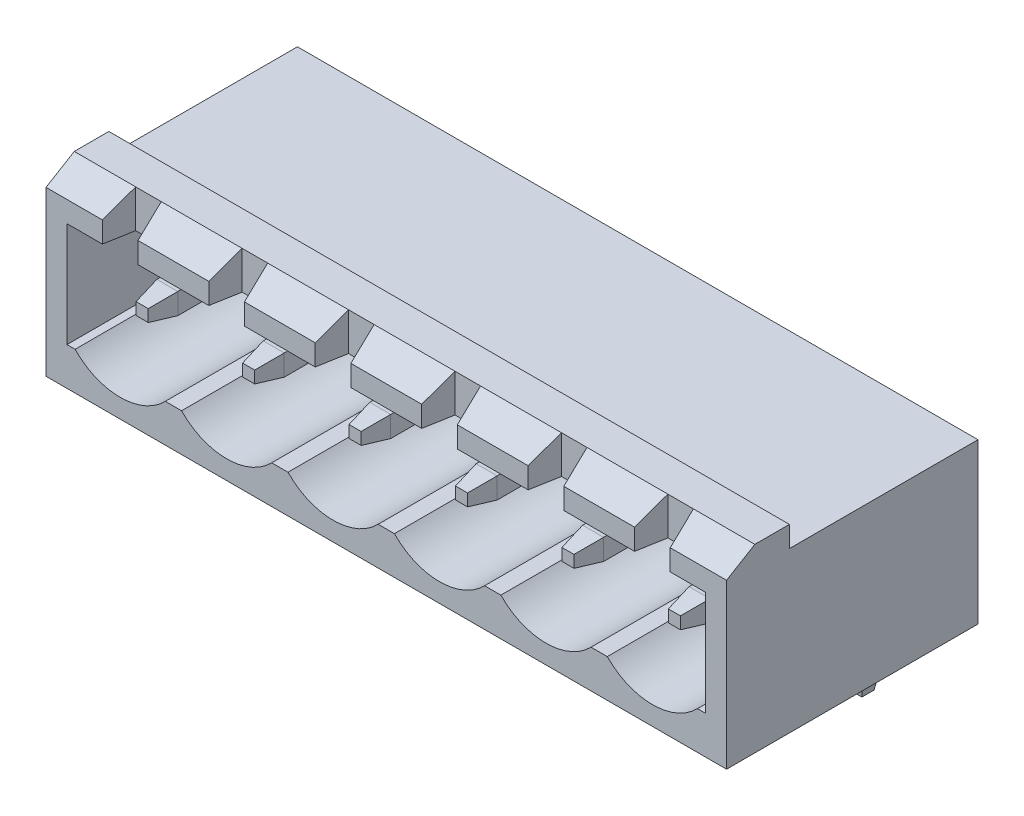
SolidWorks part; units mm, degrees
ref_plane "Front Plane" through (0, 0, 0) normal (0, 0, 1) x (1, 0, 0)
ref_plane "Top Plane" through (0, 0, 0) normal (0, 1, 0) x (1, 0, 0)
ref_plane "Right Plane" through (0, 0, 0) normal (1, 0, 0) x (0, 0, -1)
sketch "Sketch1" plane through (0, 0, 0) normal (0, 0, 1) x (1, 0, 0)
  line L1 (16.24, -3.81) -> (-16.24, -3.81)
  line L2 (16.24, -3.81) -> (16.24, 3.81)
  line L3 (16.24, 3.81) -> (-16.24, 3.81)
  line L4 (-16.24, -3.81) -> (-16.24, 3.81)
  line L5 (16.24, -3.81) -> (-16.24, 3.81) construction
  line L6 (16.24, 3.81) -> (-16.24, -3.81) construction
  point P0 (0, 0)
  dimension "D1" = 7.62
  dimension "D2" = 32.48
extrude "Boss-Extrude1" add sketch "Sketch1" along normal mid plane 12
sketch "Sketch7" plane through (16.24, 0, 0) normal (1, 0, 0) x (0, 0, -1)
  line L0 (-6, 3.81) -> (-6, 4)
  line L1 (-3, 4.81) -> (-6, 4.81) construction
  line L2 (-3, 4.81) -> (-3, 3.81) construction
  line L3 (-3, 3.81) -> (-6, 3.81) construction
  line L4 (-6, 4.81) -> (-6, 3.81) construction
  line L5 (-3, 4.81) -> (-6, 3.81) construction
  line L6 (-3, 3.81) -> (-6, 4.81) construction
  line L7 (-6, 4) -> (-4.65, 4.81)
  line L8 (-4.65, 4.81) -> (-3, 4.81)
  line L9 (-3, 4.81) -> (-3, 3.81)
  line L10 (-3, 3.81) -> (-6, 3.81)
  point P0 (-4.5, 4.31)
  point P6 (0, 0)
  dimension "D1" = 1
  dimension "D2" = 3
  dimension "D3" = 1.65
  dimension "D4" = 0.81
extrude "Boss-Extrude6" add sketch "Sketch7" against normal up to surface (32.48 mm away) up to face at (-16.24, 0, 0)
sketch "Sketch2" plane through (0, 0, 6) normal (0, 0, 1) x (1, 0, 0)
  line L0 (16.24, -3.81) -> (16.24, 4) construction
  line L1 (15.24, -2) -> (10.16, -2) construction
  line L2 (15.24, -2) -> (15.24, 3) construction
  line L3 (15.24, 3) -> (10.16, 3) construction
  line L4 (10.16, -2) -> (10.16, 3) construction
  line L5 (15.24, -2) -> (10.16, 3) construction
  line L6 (15.24, 3) -> (10.16, -2) construction
  line L7 (16.24, 3.81) -> (-16.24, 3.81) construction
  line L8 (-16.24, -3.81) -> (16.24, -3.81) construction
  line L9 (10.5478, -2) -> (10.16, -2)
  line L10 (10.16, -2) -> (10.16, 3)
  line L11 (10.16, 3) -> (15.24, 3)
  line L12 (15.24, 3) -> (15.24, -2)
  line L13 (15.24, -2) -> (14.8522, -2)
  arc A0 (10.5478, -2) -> (14.8522, -2) centre (12.7, 0.09) ccw
  point P0 (12.7, 0.5)
  point P15 (12.7, -2.91)
  dimension "D7" = 3
  dimension "D1" = 3.54
  dimension "D2" = 5.08
  dimension "D3" = 0.81
  dimension "D4" = 1.81
  dimension "D5" = 5
  dimension "D6" = 0.9
extrude "Cut-Extrude1" cut sketch "Sketch2" against normal blind 11.2
sketch "Sketch3" plane through (0, 0, -5.2) normal (0, 0, 1) x (1, 0, 0)
  line L0 (11.7, -1.028) -> (11.7, -2.7384)
  line L1 (13.7, -1.028) -> (13.7, -2.7384)
  line L2 (12.7, 0.09) -> (12.7, -0.91) construction
  line L3 (11.221, -0.16) -> (10.16, -0.16)
  line L4 (10.16, 3) -> (10.16, -2) construction
  line L5 (11.221, 0.34) -> (10.16, 0.34)
  line L6 (10.16, 0.34) -> (10.16, -0.16)
  line L7 (14.179, -0.16) -> (15.24, -0.16)
  line L8 (15.24, -2) -> (15.24, 3) construction
  line L9 (15.24, -0.16) -> (15.24, 0.34)
  line L10 (15.24, 0.34) -> (14.179, 0.34)
  line L11 (11.2, 0.09) -> (13.7, 0.09) construction
  line L12 (12.45, 1.569) -> (12.45, 3)
  line L13 (15.24, 3) -> (10.16, 3) construction
  line L14 (12.45, 3) -> (12.95, 3)
  line L15 (12.95, 3) -> (12.95, 1.569)
  line L16 (-16.24, -3.81) -> (16.24, -3.81) construction
  line L17 (12.7, -0.91) -> (12.7, -1.41) construction
  line L18 (12.7, -1.41) -> (12.7, -2.91) construction
  line L19 (13.7, 0.09) -> (14.2, 0.09) construction
  line L20 (14.2, 0.09) -> (15.24, 0.09) construction
  line L21 (10.16, 0.09) -> (11.2, 0.09) construction
  arc A0 (10.5478, -2) -> (14.8522, -2) centre (12.7, 0.09) ccw construction
  arc A1 (11.7, -2.7384) -> (13.7, -2.7384) centre (12.7, 0.09) ccw
  circle A2 centre (12.7, 0.09) radius 1 construction
  arc A3 (13.7, -1.028) -> (14.179, -0.16) centre (12.7, 0.09) ccw
  arc A4 (11.7, -1.028) -> (12.7, -1.41) centre (12.7, 0.09) ccw construction
  arc A5 (12.7, -1.41) -> (13.7, -1.028) centre (12.7, 0.09) ccw construction
  arc A6 (14.179, -0.16) -> (14.2, 0.09) centre (12.7, 0.09) ccw construction
  arc A7 (14.179, 0.34) -> (12.95, 1.569) centre (12.7, 0.09) ccw
  arc A8 (14.2, 0.09) -> (14.179, 0.34) centre (12.7, 0.09) ccw construction
  arc A9 (12.95, 1.569) -> (12.45, 1.569) centre (12.7, 0.09) ccw construction
  arc A10 (12.45, 1.569) -> (11.221, 0.34) centre (12.7, 0.09) ccw
  arc A11 (11.221, 0.34) -> (11.2, 0.09) centre (12.7, 0.09) ccw construction
  arc A12 (11.221, -0.16) -> (11.7, -1.028) centre (12.7, 0.09) ccw
  arc A13 (11.2, 0.09) -> (11.221, -0.16) centre (12.7, 0.09) ccw construction
  arc A14 (10.5478, -2) -> (11.7, -2.7384) centre (12.7, 0.09) ccw construction
  arc A15 (13.7, -2.7384) -> (14.8522, -2) centre (12.7, 0.09) ccw construction
  dimension "D1" = 2
  dimension "D2" = 3
  dimension "D3" = 2
  dimension "D4" = 0.5
  dimension "D5" = 0.5
  dimension "D6" = 3.9
  dimension "D7" = 3
extrude "Boss-Extrude2" add sketch "Sketch3" along normal blind 2.5
sketch "Sketch4" plane through (0, 0, -2.7) normal (0, 0, 1) x (1, 0, 0)
  circle A1 centre (12.7, 0.09) radius 1
  dimension "D1" = 2
extrude "Boss-Extrude3" add sketch "Sketch4" along normal offset from surface (0.7 mm away) 8
sketch "Sketch5" plane through (0, 0, -2) normal (0, 0, 1) x (1, 0, 0)
  line L1 (13.2, -0.41) -> (12.2, -0.41)
  line L2 (13.2, -0.41) -> (13.2, 0.59)
  line L3 (13.2, 0.59) -> (12.2, 0.59)
  line L4 (12.2, -0.41) -> (12.2, 0.59)
  line L5 (13.2, -0.41) -> (12.2, 0.59) construction
  line L6 (13.2, 0.59) -> (12.2, -0.41) construction
  point P0 (12.7, 0.09)
  dimension "D1" = 1
extrude "Boss-Extrude4" add sketch "Sketch5" along normal blind 5.75 separate body
sketch "Sketch6" plane through (0, 0, 3.75) normal (0, 0, 1) x (1, 0, 0)
  line L4 (12.2, 0.59) -> (12.2, -0.41)
  line L5 (12.2, -0.41) -> (13.2, -0.41)
  line L6 (13.2, -0.41) -> (13.2, 0.59)
  line L7 (13.2, 0.59) -> (12.2, 0.59)
  line L8 (12.2, 0.59) -> (12.2, -0.41)
  line L9 (12.2, -0.41) -> (13.2, -0.41)
  line L10 (13.2, -0.41) -> (13.2, 0.59)
  line L11 (13.2, 0.59) -> (12.2, 0.59)
  dimension "D1" = 0
extrude "Boss-Extrude5" add sketch "Sketch6" along normal blind 1.2 draft 10
sketch "Sketch9" plane through (0, 4.81, 0) normal (0, 1, 0) x (1, 0, 0)
  line L0 (12.7, 5.2) -> (12.7, -6) construction
  line L1 (15.24, -6) -> (10.16, -6) construction
  line L2 (11.85, -6) -> (12.09, -4.65)
  line L3 (-16.24, -4.65) -> (16.24, -4.65) construction
  line L4 (12.09, -4.65) -> (13.31, -4.65)
  line L5 (13.31, -4.65) -> (13.55, -6)
  line L6 (13.55, -6) -> (11.85, -6)
  point P2 (12.7, -4.65)
  dimension "D1" = 1.22
  dimension "D2" = 1.7
extrude "Cut-Extrude2" cut sketch "Sketch9" against normal up to next
sketch "Sketch10" plane through (0, -3.81, 0) normal (0, -1, 0) x (1, 0, 0)
  line L0 (12.7, -6) -> (12.7, 6) construction
  line L1 (-16.24, -6) -> (16.24, -6) construction
  line L2 (-16.24, 6) -> (16.24, 6) construction
  line L4 (12.2, -4.5) -> (13.2, -4.5)
  line L5 (12.2, -4.5) -> (12.2, -3.5)
  line L6 (12.2, -3.5) -> (13.2, -3.5)
  line L7 (13.2, -4.5) -> (13.2, -3.5)
  line L8 (12.2, -4.5) -> (13.2, -3.5) construction
  line L9 (12.2, -3.5) -> (13.2, -4.5) construction
  point P7 (12.7, -4)
  dimension "D1" = 10
  dimension "D2" = 1
extrude "Boss-Extrude7" add sketch "Sketch10" along normal blind 2.3 separate body
sketch "Sketch11" plane through (0, -6.11, 0) normal (0, -1, 0) x (1, 0, 0)
  line L4 (13.2, -4.5) -> (13.2, -3.5)
  line L5 (13.2, -3.5) -> (12.2, -3.5)
  line L6 (12.2, -3.5) -> (12.2, -4.5)
  line L7 (12.2, -4.5) -> (13.2, -4.5)
  line L8 (13.2, -4.5) -> (13.2, -3.5)
  line L9 (13.2, -3.5) -> (12.2, -3.5)
  line L10 (12.2, -3.5) -> (12.2, -4.5)
  line L11 (12.2, -4.5) -> (13.2, -4.5)
  dimension "D1" = 0
extrude "Boss-Extrude8" add sketch "Sketch11" along normal blind 1.2 draft 10
sketch "Sketch12" plane through (0, 0, -6) normal (0, 0, -1) x (-1, 0, 0)
  line L0 (-12.7, 0.09) -> (-12.7, -0.91) construction
  line L1 (-11.7, -3.81) -> (-13.7, -3.81)
  line L2 (-11.7, -3.81) -> (-11.7, 2.94)
  line L3 (-11.7, 2.94) -> (-13.7, 2.94)
  line L4 (-13.7, -3.81) -> (-13.7, 2.94)
  line L5 (-11.7, -3.81) -> (-13.7, 2.94) construction
  line L6 (-11.7, 2.94) -> (-13.7, -3.81) construction
  line L7 (16.24, -3.81) -> (-16.24, -3.81) construction
  point P0 (-12.7, -0.435)
  point P5 (0, 0)
  dimension "D1" = 6.75
  dimension "D2" = 2
extrude "Cut-Extrude3" cut sketch "Sketch12" against normal blind 0.5
pattern_linear "LPattern1" count 6 spacing 5.08 along (-1, 0, 0) of "Cut-Extrude1", "Boss-Extrude2", "Boss-Extrude3", "Cut-Extrude2", "Cut-Extrude3"
pattern_linear "LPattern2" count 6 spacing 5.08 along (-1, 0, 0) of bodies 111 106
equation "\"NumPins\"= 6'Number of pins on block"
equation "\"PinPitch\"= .2in'distance between pin centers"
equation "\"TerminalHeight\"= .3in'height of block"
equation "\"TerminalDepth\"= 12mm'depth of block"
equation "\"SideOffset\"= 1mm'offset on edges to provide space for side walls"
equation "\"PinSize\"= 1mm'side length of pin square profile"
equation "\"TerminalWidth\"= ( 2 * \"SideOffset\" ) + ( \"NumPins\" * \"PinPitch\" )"
equation "\"D2@Sketch1\"=\"NumPins\"*\"PinPitch\"+2*\"SideOffset\""
equation "\"D3@LPattern1\"=\"PinPitch\""
equation "\"D1@LPattern1\"=\"NumPins\""
equation "\"D2@Sketch10\"=\"PinSize\""
equation "\"D3@LPattern2\"=\"PinPitch\""
equation "\"D1@LPattern2\"=\"NumPins\""
